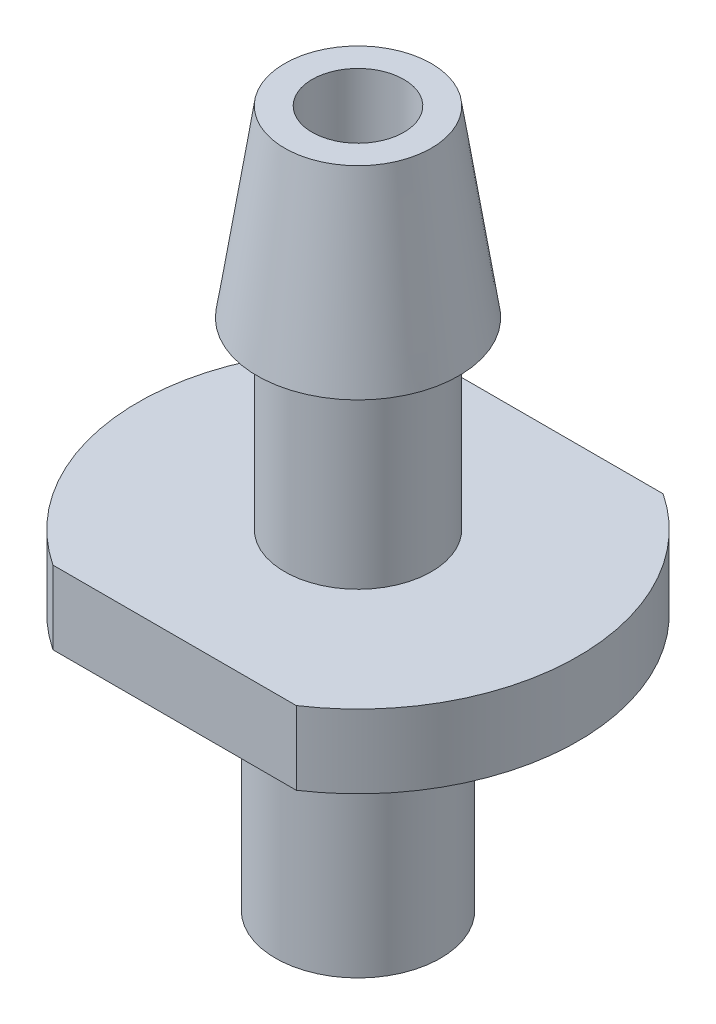
SolidWorks part; units mm, degrees
ref_plane "Спереди" through (0, 0, 0) normal (0, 0, 1) x (1, 0, 0)
ref_plane "Сверху" through (0, 0, 0) normal (0, 1, 0) x (1, 0, 0)
ref_plane "Справа" through (0, 0, 0) normal (1, 0, 0) x (0, 0, -1)
sketch "Эскиз1" plane through (0, 0, 0) normal (0, 0, 1) x (1, 0, 0)
  line L0 (0, 0) -> (-1.25, 0) construction
  line L1 (0, 0) -> (0, 2.4033) construction
  line L2 (-1.25, 0) -> (-2.25, 0)
  line L3 (-2.25, 0) -> (-2.25, 7)
  line L4 (-2.25, 7) -> (-6, 7)
  line L5 (-6, 7) -> (-6, 9)
  line L6 (-6, 9) -> (-2, 9)
  line L7 (-2, 9) -> (-2, 14)
  line L8 (-2, 14) -> (-2.75, 14)
  line L9 (-2.75, 14) -> (-2, 19)
  line L10 (-2, 19) -> (-1.25, 19)
  line L11 (-1.25, 19) -> (-1.25, 0)
  point P14 (-1.0967, 0)
  dimension "D1" = 4.5
  dimension "D2" = 2.5
  dimension "D3" = 12
  dimension "D4" = 4
  dimension "D5" = 5.5
  dimension "D6" = 4
  dimension "D7" = 5
  dimension "D8" = 2
  dimension "D9" = 19
  dimension "D10" = 7
revolve "Повернуть1" add sketch "Эскиз1" angle 360 about L1
sketch "Эскиз2" plane through (0, 9, 0) normal (0, 1, 0) x (1, 0, 0)
  line L0 (0, 0) -> (0, -5.7189) construction
  line L1 (0, 0) -> (-6, 0) construction
  line L2 (-5.9018, -5) -> (5.9018, -5)
  line L3 (-5.9018, -5) -> (-5.9018, -6.4378)
  line L4 (-5.9018, -6.4378) -> (5.9018, -6.4378)
  line L5 (5.9018, -5) -> (5.9018, -6.4378)
  line L6 (-5.9018, -5) -> (5.9018, -6.4378) construction
  line L7 (-5.9018, -6.4378) -> (5.9018, -5) construction
  line L8 (-5.9018, 6.4378) -> (5.9018, 5) construction
  line L9 (-5.9018, 5) -> (5.9018, 6.4378) construction
  line L10 (5.9018, 5) -> (5.9018, 6.4378)
  line L11 (-5.9018, 6.4378) -> (5.9018, 6.4378)
  line L12 (-5.9018, 5) -> (-5.9018, 6.4378)
  line L13 (-5.9018, 5) -> (5.9018, 5)
  circle A0 centre (0, 0) radius 6 construction
  dimension "D1" = 10
extrude "Вырез-Вытянуть1" cut sketch "Эскиз2" against normal blind 10
